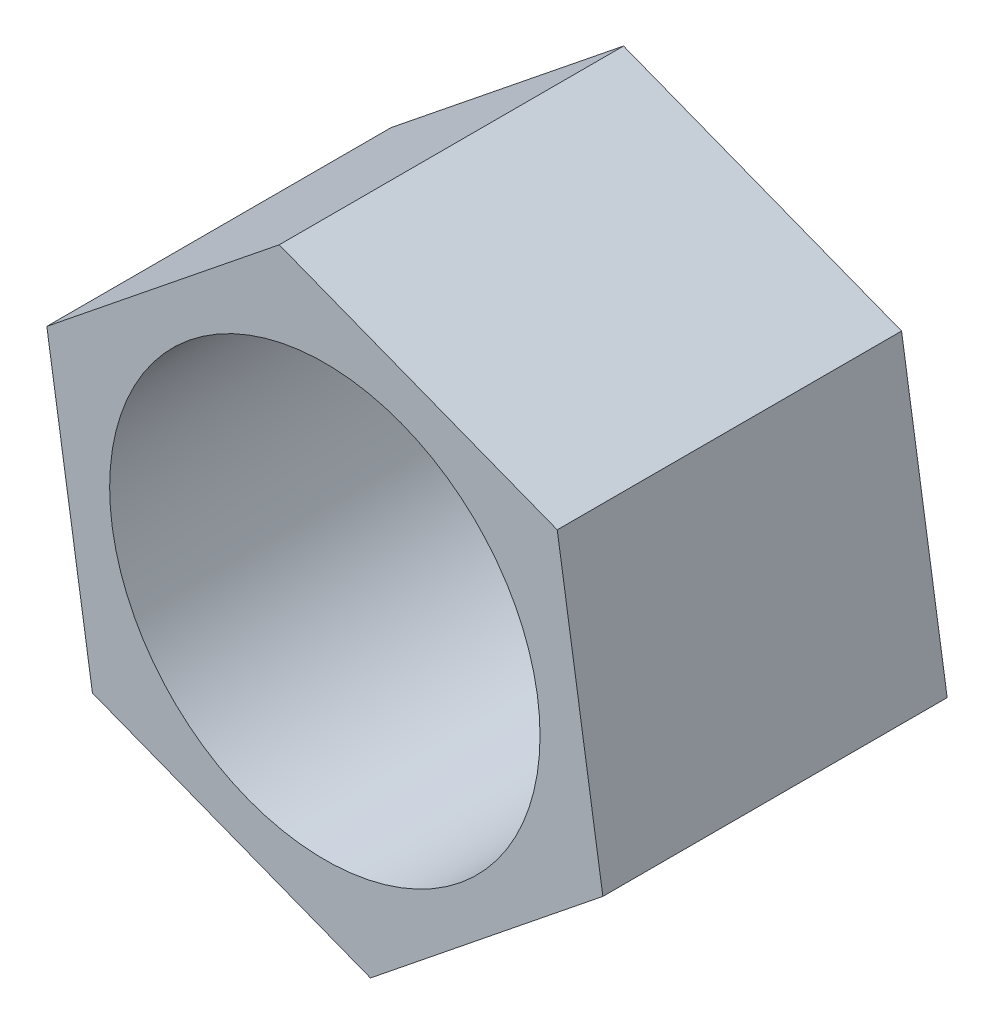
SolidWorks part; units mm, degrees
ref_plane "Front Plane" through (0, 0, 0) normal (0, 0, 1) x (1, 0, 0)
ref_plane "Top Plane" through (0, 0, 0) normal (0, 1, 0) x (1, 0, 0)
ref_plane "Right Plane" through (0, 0, 0) normal (1, 0, 0) x (0, 0, -1)
sketch "Sketch1" plane through (0, 0, 0) normal (0, 0, 1) x (1, 0, 0)
  line L1 (-0.5298, 3.4233) -> (-3.2296, 1.2528)
  line L2 (-3.2296, 1.2528) -> (-2.6998, -2.1705)
  line L3 (-2.6998, -2.1705) -> (0.5298, -3.4233)
  line L4 (0.5298, -3.4233) -> (3.2296, -1.2528)
  line L5 (3.2296, -1.2528) -> (2.6998, 2.1705)
  line L6 (2.6998, 2.1705) -> (-0.5298, 3.4233)
  circle A0 centre (0, 0) radius 3 construction
  circle A1 centre (0, 0) radius 2.5
  dimension "D1" = 6
  dimension "D2" = 5
extrude "Boss-Extrude1" add sketch "Sketch1" along normal blind 4
